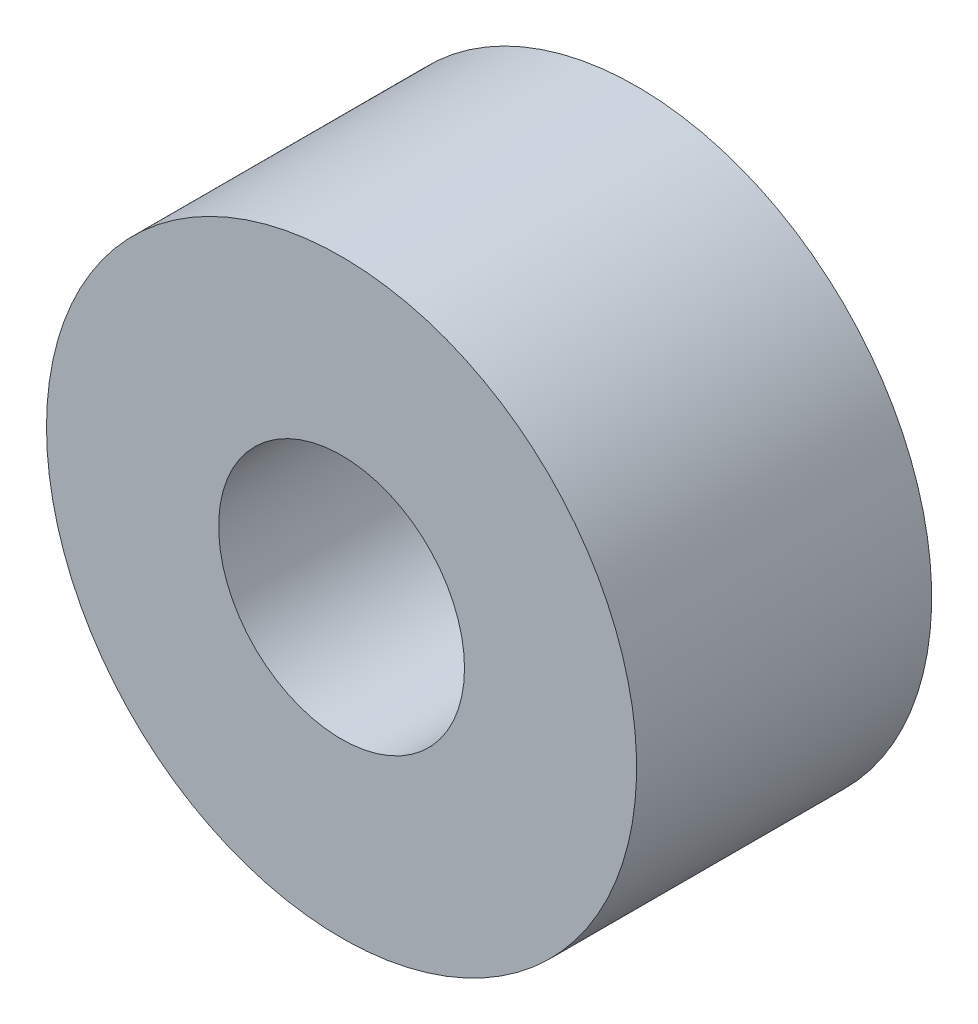
SolidWorks part; units mm, degrees
material "Pine"
ref_plane "Front Plane" through (0, 0, 0) normal (0, 0, 1) x (1, 0, 0)
ref_plane "Top Plane" through (0, 0, 0) normal (0, 1, 0) x (1, 0, 0)
ref_plane "Right Plane" through (0, 0, 0) normal (1, 0, 0) x (0, 0, -1)
sketch "Sketch1" plane through (0, 0, 0) normal (0, 0, 1) x (1, 0, 0)
  circle A0 centre (0, 0) radius 19.05
  dimension "D1" = 38.1
extrude "Boss-Extrude1" add sketch "Sketch1" along normal blind 19.05
sketch "Sketch2" plane through (0, 0, 19.05) normal (0, 0, 1) x (1, 0, 0)
  circle A0 centre (0, 0) radius 7.9375
  dimension "D1" = 15.875
extrude "Cut-Extrude1" cut sketch "Sketch2" against normal through all
